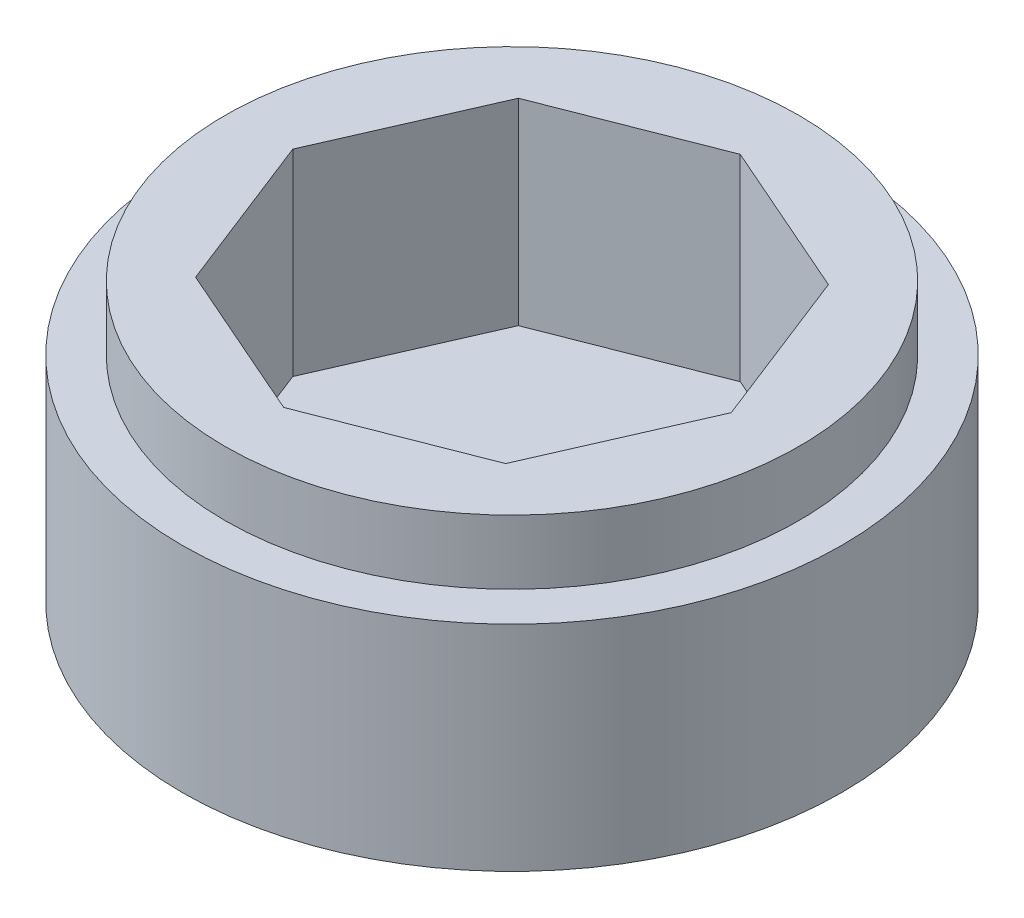
SolidWorks part; units mm, degrees
material "ABS"
ref_plane "Front Plane" through (0, 0, 0) normal (0, 0, 1) x (1, 0, 0)
ref_plane "Top Plane" through (0, 0, 0) normal (0, 1, 0) x (1, 0, 0)
ref_plane "Right Plane" through (0, 0, 0) normal (1, 0, 0) x (0, 0, -1)
sketch "Sketch1" plane through (0, 0, 0) normal (0, 1, 0) x (1, 0, 0)
  circle A0 centre (0, 0) radius 3.85
  dimension "D1" = 7.7
extrude "Boss-Extrude1" add sketch "Sketch1" along normal blind 2.5
sketch "Sketch2" plane through (0, 2.5, 0) normal (0, 1, 0) x (1, 0, 0)
  circle A0 centre (0, 0) radius 3.35
  circle A1 centre (0, 0) radius 3.85 construction
  dimension "D1" = 0.5
extrude "Boss-Extrude2" add sketch "Sketch2" along normal blind 0.75
sketch "Sketch3" plane through (0, 3.25, 0) normal (0, 1, 0) x (1, 0, 0)
  line L20 (-0.0526, -2.6126) -> (1.8102, -1.8846)
  line L21 (1.8102, -1.8846) -> (2.6126, -0.0526)
  line L22 (2.6126, -0.0526) -> (1.8846, 1.8102)
  line L23 (1.8846, 1.8102) -> (0.0526, 2.6126)
  line L24 (0.0526, 2.6126) -> (-1.8102, 1.8846)
  line L25 (-1.8102, 1.8846) -> (-2.6126, 0.0526)
  line L26 (-2.6126, 0.0526) -> (-1.8846, -1.8102)
  line L27 (-1.8846, -1.8102) -> (-0.0526, -2.6126)
  circle A4 centre (0, 0) radius 2.4142 construction
  circle A11 centre (0, 0) radius 3.35 construction
  point P1 (0, 0)
  point P11 (2.6126, -0.0526)
  point P12 (3.3496, -0.0526)
  point P14 (0, 0)
  dimension "D1" = 2
extrude "Cut-Extrude1" cut sketch "Sketch3" against normal blind 2.3
